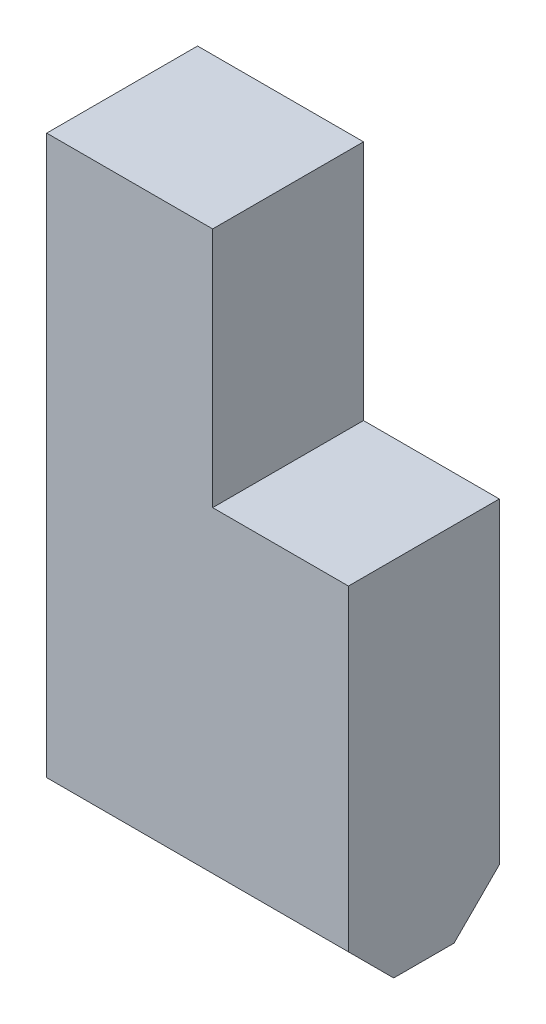
SolidWorks part; units mm, degrees
ref_plane "Front" through (0, 0, 0) normal (0, 0, 1) x (1, 0, 0)
ref_plane "Top" through (0, 0, 0) normal (0, 1, 0) x (1, 0, 0)
ref_plane "Right" through (0, 0, 0) normal (1, 0, 0) x (0, 0, -1)
sketch "Sketch1" plane through (0, 0, 0) normal (0, 0, 1) x (1, 0, 0)
  line L0 (20, 24) -> (11, 24)
  line L1 (0, 0) -> (20, 0)
  line L2 (0, 0) -> (0, 40)
  line L3 (0, 40) -> (11, 40)
  line L4 (20, 0) -> (20, 24)
  line L5 (11, 24) -> (11, 40)
  dimension "D1" = 20
  dimension "D2" = 40
  dimension "D3" = 9
  dimension "D4" = 16
extrude "Boss-Extrude1" add sketch "Sketch1" along normal mid plane 10
chamfer "Chamfer1" distance 3 angle 45 2 edges at (10, 0, 5) (10, 0, -5)
sketch "Sketch2" plane through (0, 0, 0) normal (0, -1, 0) x (1, 0, 0)
  line L0 (20, 2) -> (20, -2) construction
  line L1 (20, 0) -> (24, 0)
  line L2 (20, 0) -> (20, -4)
  dimension "D1" = 4
